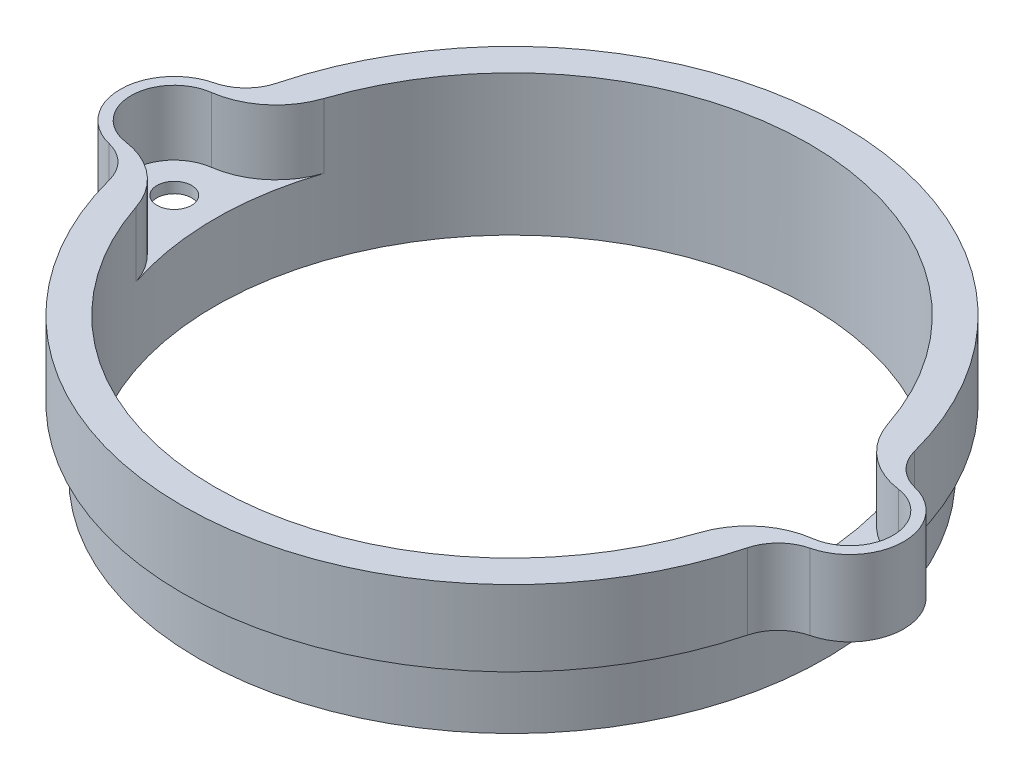
SolidWorks part; units mm, degrees
ref_plane "Front Plane" through (0, 0, 0) normal (0, 0, 1) x (1, 0, 0)
ref_plane "Top Plane" through (0, 0, 0) normal (0, 1, 0) x (1, 0, 0)
ref_plane "Right Plane" through (0, 0, 0) normal (1, 0, 0) x (0, 0, -1)
sketch "Sketch1" plane through (0, 0, 0) normal (0, 1, 0) x (1, 0, 0)
  circle A0 centre (0, 0) radius 29
  circle A1 centre (0, 0) radius 27.5
  dimension "D1" = 58
  dimension "D2" = 1.5
extrude "Boss-Extrude1" add sketch "Sketch1" along normal blind 6
sketch "Sketch3" plane through (0, 6, 0) normal (0, 1, 0) x (1, 0, 0)
  circle A0 centre (0, 0) radius 27.5
  circle A1 centre (0, 0) radius 30.5
  circle A2 centre (0, 0) radius 29 construction
  dimension "D1" = 3
  dimension "D2" = 1.5
extrude "Boss-Extrude3" add sketch "Sketch3" along normal blind 7
sketch "Sketch4" plane through (0, 13, 0) normal (0, 1, 0) x (1, 0, 0)
  arc A0 (-27.469, 1.3054) -> (-27.469, -1.3054) centre (-31.25, 0) ccw
  arc A1 (-30.2377, 3.9914) -> (-30.2377, -3.9914) centre (0, 0) ccw
  circle A2 centre (0, 0) radius 27.5
  arc A3 (-32.4294, 4.8589) -> (-32.4294, -4.8589) centre (-31.25, 0) ccw
  arc A4 (-29.5037, -7.732) -> (-29.5037, 7.732) centre (0, 0) ccw
  arc A5 (-29.5037, -7.732) -> (-32.4294, -4.8589) centre (-33.373, -8.746) ccw
  arc A6 (-29.5037, 7.732) -> (-32.4294, 4.8589) centre (-33.373, 8.746) cw
  circle A8 centre (-31.25, 0) radius 1.6
  circle A9 centre (0, 0) radius 30.5 construction
  circle A10 centre (0, 0) radius 27.5 construction
  point P18 (-27.588, 2.3899)
  point P19 (0, 0)
  point P20 (-27.4665, 1.3575)
  point P23 (-27.4692, -1.3001)
  circle M1 centre (0, 0) radius 30.5
  dimension "D1" = 8
  dimension "D3" = 4
  dimension "D5" = 5
  dimension "D7" = 55
  dimension "D8" = 30.5
  dimension "D2" = 3.2
  dimension "D4" = 31.25
extrude "Boss-Extrude4" add sketch "Sketch4" against normal blind 6 contours A6 A3 A5 A0 M1
sketch "Sketch6" plane through (0, 13, 0) normal (0, 1, 0) x (1, 0, 0)
  circle A0 centre (-31.25, 0) radius 4
  arc A1 (-30.253, 3.8738) -> (-30.253, -3.8738) centre (-31.25, 0) ccw construction
  dimension "D1" = 0
extrude "Cut-Extrude1" cut sketch "Sketch6" against normal blind 7
sketch "Sketch8" plane through (0, 7, 0) normal (0, -1, 0) x (1, 0, 0)
  circle A0 centre (-31.25, 0) radius 4
  circle A1 centre (-31.25, 0) radius 1.6
  arc A5 (-30.253, -3.8738) -> (-29.5037, -7.732) centre (0, 0) ccw
  arc A11 (-29.5037, -7.732) -> (-32.4294, -4.8589) centre (-33.373, -8.746) ccw
  arc A17 (-29.5037, -7.732) -> (-32.4294, -4.8589) centre (-33.373, -8.746) ccw
  arc A19 (-30.253, -3.8738) -> (-29.5037, -7.732) centre (0, 0) ccw
  arc A21 (-32.4294, 4.8589) -> (-29.5037, 7.732) centre (-33.373, 8.746) ccw
  arc A22 (-32.4294, 4.8589) -> (-29.5037, 7.732) centre (-33.373, 8.746) ccw
  arc A23 (-32.4294, 4.8589) -> (-32.4294, -4.8589) centre (-31.25, 0) ccw
  arc A24 (-32.4294, 4.8589) -> (-32.4294, -4.8589) centre (-31.25, 0) ccw
  arc A25 (-30.253, 3.8738) -> (-30.253, -3.8738) centre (-31.25, 0) ccw
  arc A26 (-30.253, 3.8738) -> (-30.253, -3.8738) centre (-31.25, 0) ccw
  arc A27 (-29.5037, 7.732) -> (-30.253, 3.8738) centre (0, 0) ccw
  arc A28 (-29.5037, 7.732) -> (-30.253, 3.8738) centre (0, 0) ccw
  arc M7 (-29.5037, -7.732) -> (-30.253, -3.8738) centre (0, 0) cw
  arc M8 (-30.253, -3.8738) -> (-30.253, 3.8738) centre (-31.25, 0) cw
  arc M9 (-30.253, 3.8738) -> (-29.5037, 7.732) centre (0, 0) cw
  arc M10 (-29.5037, 7.732) -> (-32.4294, 4.8589) centre (-33.373, 8.746) cw
  arc M11 (-32.4294, 4.8589) -> (-32.4294, -4.8589) centre (-31.25, 0) ccw
  arc M12 (-32.4294, -4.8589) -> (-29.5037, -7.732) centre (-33.373, -8.746) cw
  dimension "D2" = 3.2
  dimension "D3" = 8
  dimension "D1" = 0
extrude "Boss-Extrude5" add sketch "Sketch8" along normal blind 1 contours A0 A1 M7 M9 M8 | A0 M11 M7 M8 M9 | A0 M12 M7 | A0 M9 M10
sketch "Sketch9" plane through (0, 13, 0) normal (0, 1, 0) x (1, 0, 0)
  arc A0 (-26.0915, -8.6881) -> (-26.0915, 8.6881) centre (0, 0) ccw
  arc A1 (-26.0915, -8.6881) -> (-31.7893, -3.9635) centre (-32.733, -10.8996) ccw
  arc A2 (-27.469, -1.3054) -> (-27.469, 1.3054) centre (-31.25, 0) ccw
  arc A3 (-27.469, 1.3054) -> (-27.469, -1.3054) centre (-31.25, 0) ccw
  arc A5 (-31.7893, 3.9635) -> (-31.7893, -3.9635) centre (-31.25, 0) ccw
  arc A6 (-26.0915, 8.6881) -> (-31.7893, 3.9635) centre (-32.733, 10.8996) cw
  arc A8 (-29.5037, -7.732) -> (-29.5037, 7.732) centre (0, 0) ccw
  arc A13 (-32.4294, 4.8589) -> (-29.5037, 7.732) centre (-33.373, 8.746) ccw
  arc A14 (-32.4294, 4.8589) -> (-32.4294, -4.8589) centre (-31.25, 0) ccw
  arc A15 (-29.5037, -7.732) -> (-32.4294, -4.8589) centre (-33.373, -8.746) ccw
  arc A16 (-29.5037, -7.732) -> (-29.5037, 7.732) centre (0, 0) ccw
  arc A21 (-32.4294, 4.8589) -> (-29.5037, 7.732) centre (-33.373, 8.746) ccw
  arc A22 (-32.4294, 4.8589) -> (-32.4294, -4.8589) centre (-31.25, 0) ccw
  arc A23 (-29.5037, -7.732) -> (-32.4294, -4.8589) centre (-33.373, -8.746) ccw
  arc M11 (-27.469, 1.3054) -> (-27.469, -1.3054) centre (0, 0) cw
  arc M13 (-27.469, 1.3054) -> (-27.469, -1.3054) centre (0, 0) cw
  arc M14 (-27.469, -1.3054) -> (-27.469, 1.3054) centre (-31.25, 0) cw
  dimension "D4" = 7
  dimension "D1" = 0
  dimension "D2" = 0
extrude "Cut-Extrude2" cut sketch "Sketch9" along a picked direction on the side against the normal blind 6 contours A6 M11 M14 | A1 M13 M14
sketch "Sketch10" plane through (0, 7, 0) normal (0, 1, 0) x (1, 0, 0)
  circle A0 centre (0, 0) radius 27.5
  arc A7 (-27.469, -1.3054) -> (-27.469, 1.3054) centre (-31.25, 0) ccw
  arc A8 (-26.0915, 8.6881) -> (-27.469, 1.3054) centre (0, 0) ccw
  arc A9 (-31.7893, 3.9635) -> (-26.0915, 8.6881) centre (-32.733, 10.8996) ccw
  arc A10 (-31.7893, 3.9635) -> (-31.7893, -3.9635) centre (-31.25, 0) ccw
  arc A11 (-26.0915, -8.6881) -> (-31.7893, -3.9635) centre (-32.733, -10.8996) ccw
  arc A12 (-27.469, -1.3054) -> (-26.0915, -8.6881) centre (0, 0) ccw
  arc A13 (-27.469, -1.3054) -> (-27.469, 1.3054) centre (-31.25, 0) ccw
  arc A14 (-26.0915, 8.6881) -> (-27.469, 1.3054) centre (0, 0) ccw
  arc A15 (-31.7893, 3.9635) -> (-26.0915, 8.6881) centre (-32.733, 10.8996) ccw
  arc A16 (-31.7893, 3.9635) -> (-31.7893, -3.9635) centre (-31.25, 0) ccw
  arc A17 (-26.0915, -8.6881) -> (-31.7893, -3.9635) centre (-32.733, -10.8996) ccw
  arc A18 (-27.469, -1.3054) -> (-26.0915, -8.6881) centre (0, 0) ccw
  dimension "D1" = 0
extrude "Cut-Extrude3" cut sketch "Sketch10" against normal blind 10
pattern_circular "CirPattern1" count 2 over 360 about axis through (0, 0, 0) along (0, 1, 0) of "Boss-Extrude4", "Cut-Extrude1", "Boss-Extrude5", "Cut-Extrude2", "Cut-Extrude3"
